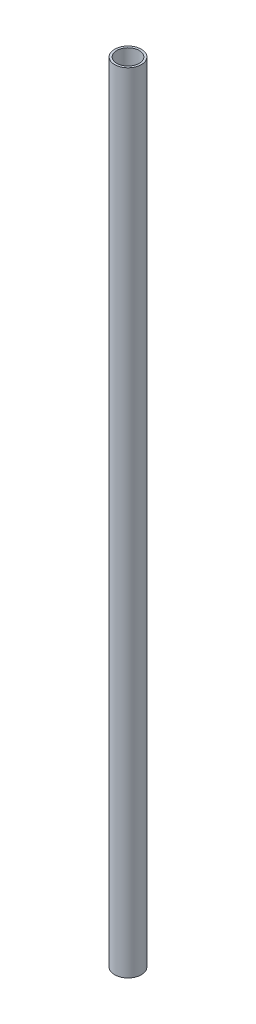
SolidWorks part; units mm, degrees
ref_plane "Front Plane" through (0, 0, 0) normal (0, 0, 1) x (1, 0, 0)
ref_plane "Top Plane" through (0, 0, 0) normal (0, 1, 0) x (1, 0, 0)
ref_plane "Right Plane" through (0, 0, 0) normal (1, 0, 0) x (0, 0, -1)
sketch "Sketch1" plane through (0, 0, 0) normal (0, 1, 0) x (1, 0, 0)
  circle A0 centre (0, 0) radius 12.5
  circle A1 centre (0, 0) radius 10.5
  dimension "D1" = 25
  dimension "D2" = 21
extrude "Boss-Extrude1" add sketch "Sketch1" along normal blind 738
equation "\"cf_tube_outer_diameter\" = 25mm"
equation "\"cf_tube_inner_diameter\" = 21mm"
equation "\"mid_plate_mid_to_top\" = 100mm"
equation "\"mid_plate_mid_to_bottom\" = 125mm"
equation "\"mid_plate_horizontal_spacing\" = 250mm"
equation "\"mid_tube_length\" = 500mm"
equation "\"D2@Sketch1\"=\"cf_tube_inner_diameter\""
equation "\"D1@Sketch1\"=\"cf_tube_outer_diameter\""
